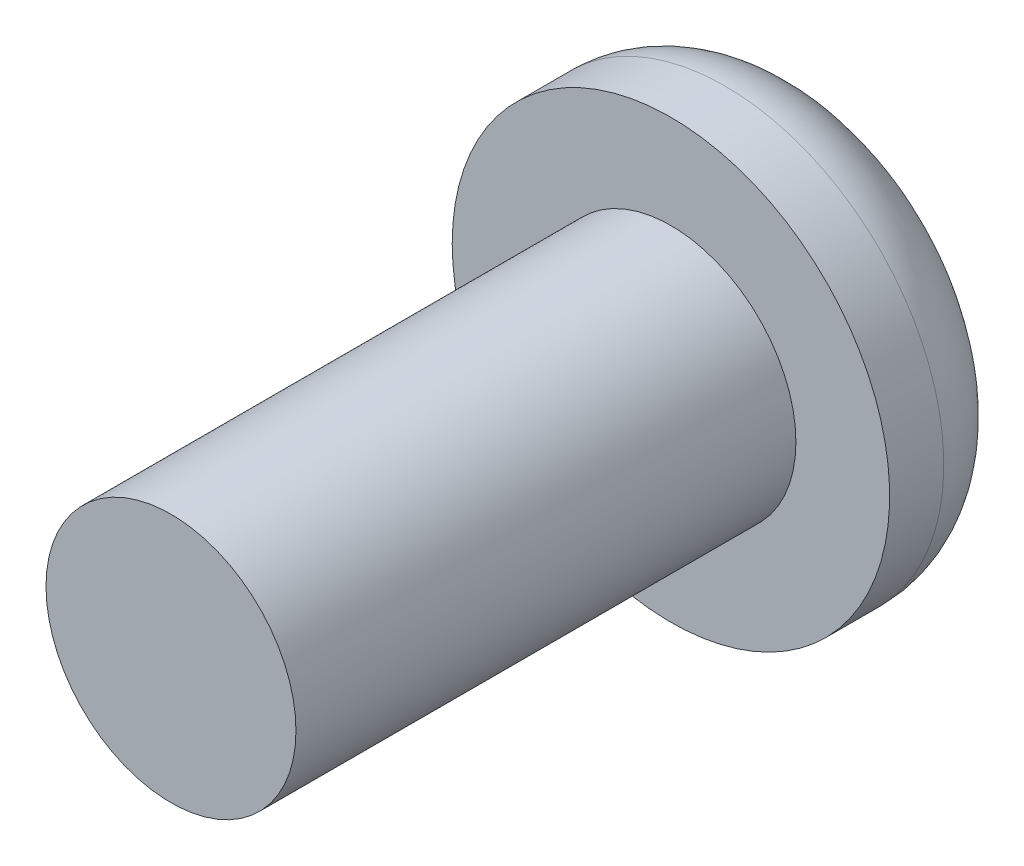
SolidWorks part; units mm, degrees
ref_plane "前视基准面" through (0, 0, 0) normal (0, 0, 1) x (1, 0, 0)
ref_plane "上视基准面" through (0, 0, 0) normal (0, 1, 0) x (1, 0, 0)
ref_plane "右视基准面" through (0, 0, 0) normal (1, 0, 0) x (0, 0, -1)
sketch "草图1" plane through (0, 0, 0) normal (0, 0, 1) x (1, 0, 0)
  circle A0 centre (0, 0) radius 3
extrude "凸台-拉伸1" add sketch "草图1" along normal blind 12
sketch "草图2" plane through (0, 0, 0) normal (0, 0, -1) x (-1, 0, 0)
  circle A0 centre (0, 0) radius 5.25
extrude "凸台-拉伸2" add sketch "草图2" along normal blind 3.3
fillet "圆角1" radius 2 1 edges at (-5.25, 0, -3.3)
